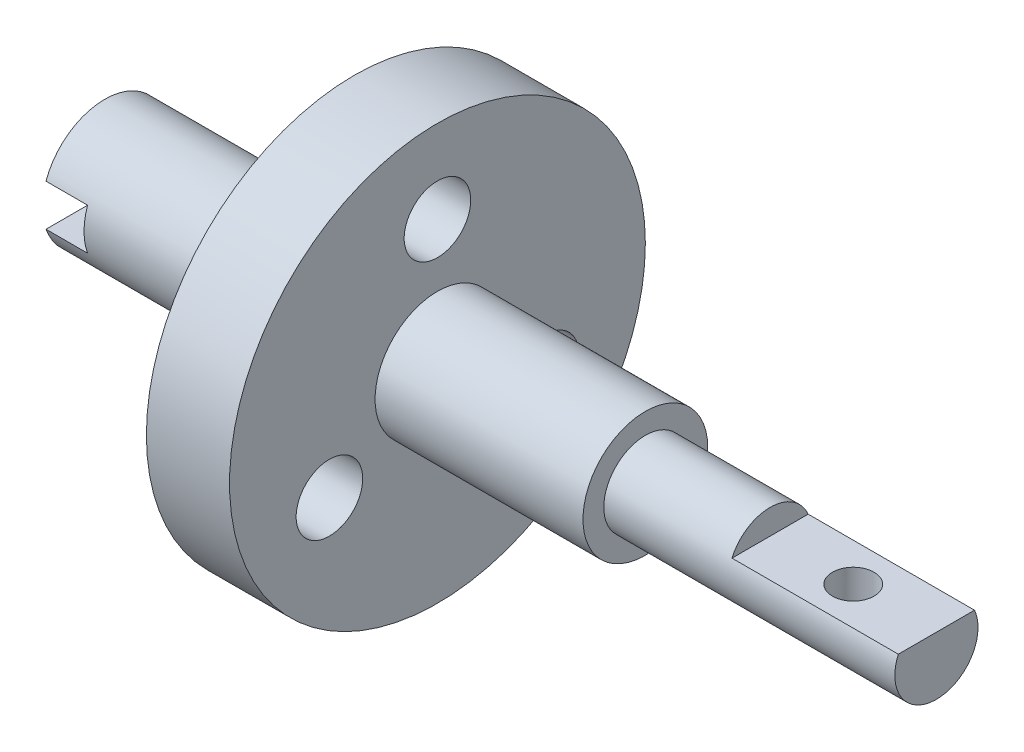
SolidWorks part; units mm, degrees
material "AISI 304"
ref_plane "Front Plane" through (0, 0, 0) normal (0, 0, 1) x (1, 0, 0)
ref_plane "Top Plane" through (0, 0, 0) normal (0, 1, 0) x (1, 0, 0)
ref_plane "Right Plane" through (0, 0, 0) normal (1, 0, 0) x (0, 0, -1)
sketch "Sketch1" plane through (0, 0, 0) normal (1, 0, 0) x (0, 0, -1)
  circle A0 centre (0, 0) radius 25
  dimension "D1" = 50
extrude "Boss-Extrude3" add sketch "Sketch1" along normal blind 60 and the other way blind 40
sketch "Sketch2" plane through (60, 0, 0) normal (1, 0, 0) x (0, 0, -1)
  circle A0 centre (0, 0) radius 7.5
  dimension "D1" = 15
extrude "Cut-Extrude3" cut sketch "Sketch2" against normal blind 60 flip side to cut
sketch "Sketch4" plane through (-40, 0, 0) normal (-1, 0, 0) x (0, 0, 1)
  circle A0 centre (0, 0) radius 7.5
  dimension "D1" = 15
extrude "Cut-Extrude4" cut sketch "Sketch4" against normal blind 30 flip side to cut
sketch "Sketch5" plane through (60, 0, 0) normal (1, 0, 0) x (0, 0, -1)
  circle A0 centre (0, 0) radius 5
  dimension "D1" = 10
extrude "Cut-Extrude5" cut sketch "Sketch5" against normal blind 35 flip side to cut
sketch "Sketch6" plane through (60, 0, 0) normal (1, 0, 0) x (0, 0, -1)
  line L0 (-4.5826, 2) -> (4.5826, 2)
  circle A0 centre (0, 0) radius 5 construction
  arc A1 (-4.5826, 2) -> (4.5826, 2) centre (0, 0) cw
  point P4 (0, 2)
  circle M2 centre (0, 0) radius 5
  dimension "D1" = 2
extrude "Cut-Extrude6" cut sketch "Sketch6" against normal blind 20 contours L0 M2
sketch "Sketch7" plane through (0, 2, 0) normal (0, 1, 0) x (1, 0, 0)
  line L0 (0, 0) -> (63.3016, 0) construction
  line L1 (60, -4.5826) -> (60, 4.5826) construction
  circle A0 centre (50, 0) radius 2.5
  dimension "D2" = 5
  dimension "D1" = 10
extrude "Cut-Extrude7" cut sketch "Sketch7" against normal through all
sketch "Sketch8" plane through (0, 0, 0) normal (1, 0, 0) x (0, 0, -1)
  arc A0 (-14.5106, -3.8002) -> (-10.5464, -10.6665) centre (0, 0) ccw construction
  circle A1 centre (0, 15) radius 4
  arc A2 (-14.5106, -3.8002) -> (10.5464, -10.6665) centre (0, 0) ccw construction
  circle A3 centre (12.9904, -7.5) radius 4
  arc A4 (-14.5106, -3.8002) -> (3.9643, 14.4667) centre (0, 0) ccw construction
  circle A5 centre (-12.9904, -7.5) radius 4
  arc A6 (3.9643, 14.4667) -> (-3.9643, 14.4667) centre (0, 0) ccw construction
  arc A7 (3.9643, 14.4667) -> (-3.9643, 14.4667) centre (0, 0) ccw construction
  arc A8 (10.5464, -10.6665) -> (14.5106, -3.8002) centre (0, 0) ccw construction
  point P14 (0, 0)
  dimension "D1" = 30
  dimension "D2" = 8
  dimension "D3" = 3
extrude "Cut-Extrude8" cut sketch "Sketch8" against normal blind 20
sketch "Sketch11" plane through (-40, 0, 0) normal (-1, 0, 0) x (0, 0, 1)
  line L0 (0, 0) -> (9.7498, 0) construction
  line L1 (-7.0711, 2.5) -> (7.0711, 2.5)
  line L2 (-7.0711, -2.5) -> (7.0711, -2.5)
  circle A0 centre (0, 0) radius 7.5 construction
  arc A1 (-7.0711, 2.5) -> (7.0711, 2.5) centre (0, 0) cw
  arc A2 (-7.0711, -2.5) -> (7.0711, -2.5) centre (0, 0) ccw
  dimension "D1" = 5
extrude "Cut-Extrude10" cut sketch "Sketch11" against normal blind 5
